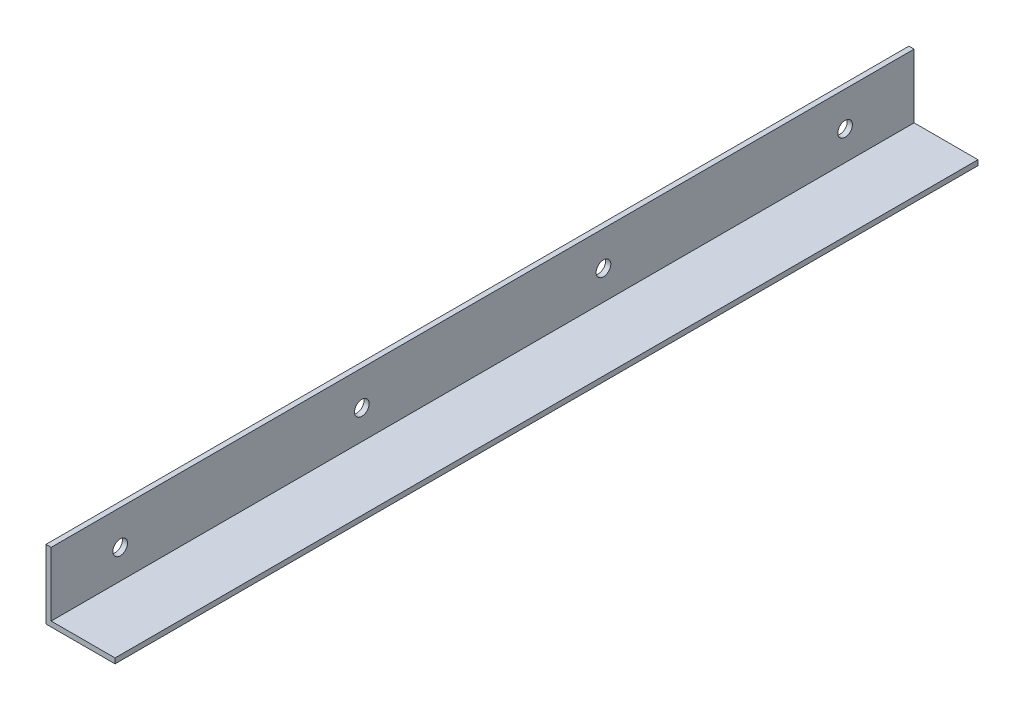
SolidWorks part; units mm, degrees
material "1060-H12"
ref_plane "Ön Düzlem" through (0, 0, 0) normal (0, 0, 1) x (1, 0, 0)
ref_plane "Üst Düzlem" through (0, 0, 0) normal (0, 1, 0) x (1, 0, 0)
ref_plane "Sağ Düzlem" through (0, 0, 0) normal (1, 0, 0) x (0, 0, -1)
sketch "Çizim1" plane through (0, 0, 0) normal (0, 0, 1) x (1, 0, 0)
  line L0 (0, 0) -> (0, 40)
  line L1 (0, 0) -> (40, 0)
  line L2 (3, 3) -> (40, 3)
  line L3 (3, 3) -> (3, 40)
  line L4 (0, 40) -> (3, 40)
  line L5 (40, 3) -> (40, 0)
  dimension "D1" = 40
  dimension "D2" = 40
  dimension "D3" = 3
extrude "Yükseklik-Ekstrüzyon1" add sketch "Çizim1" along normal blind 500
sketch "Çizim2" plane through (0, 0, 0) normal (-1, 0, 0) x (0, 0, 1)
  line L0 (0, 40) -> (0, 0) construction
  line L1 (500, 40) -> (500, 0) construction
  line L2 (500, 40) -> (0, 40) construction
  circle A0 centre (40, 20) radius 4.25
  circle A1 centre (180, 20) radius 4.25
  circle A2 centre (320, 20) radius 4.25
  circle A3 centre (460, 20) radius 4.25
  dimension "D1" = 8.5
  dimension "D3" = 40
  dimension "D4" = 140
  dimension "D5" = 140
  dimension "D6" = 20
  dimension "D2" = 40
extrude "Kes-Ekstrüzyon1" cut sketch "Çizim2" against normal blind 10
